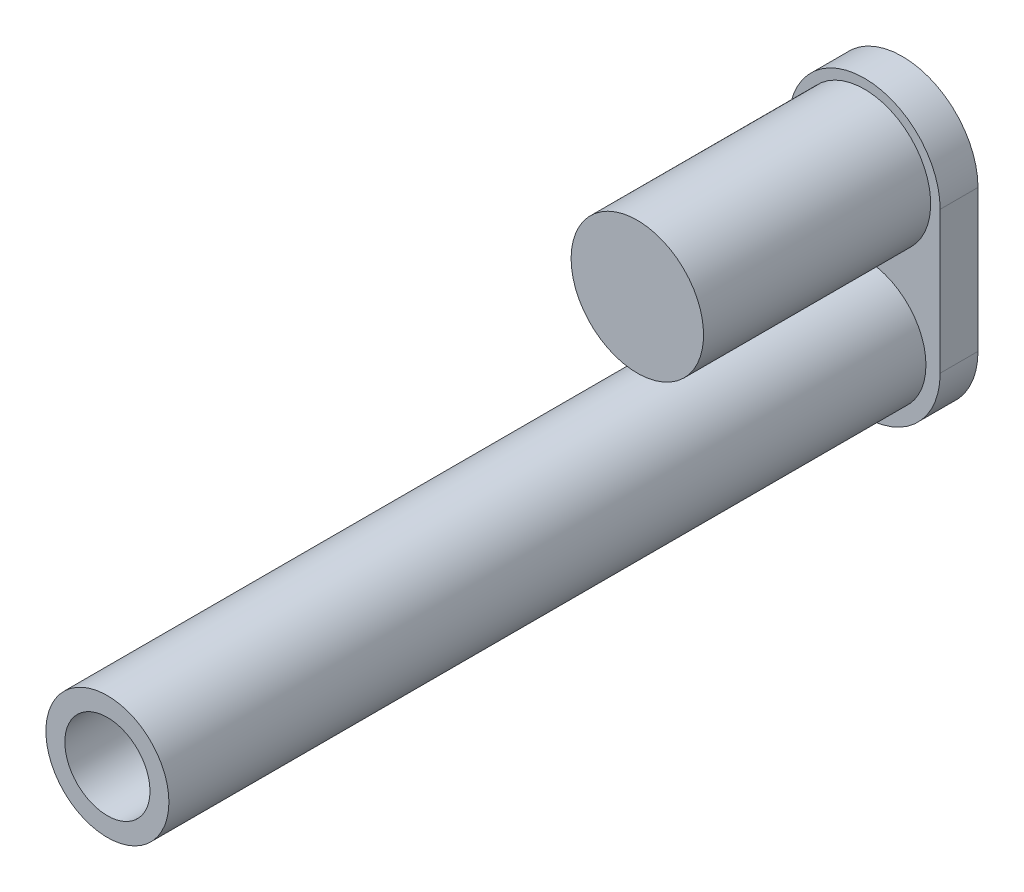
SolidWorks part; units mm, degrees
ref_plane "Front Plane" through (0, 0, 0) normal (0, 0, 1) x (1, 0, 0)
ref_plane "Top Plane" through (0, 0, 0) normal (0, 1, 0) x (1, 0, 0)
ref_plane "Right Plane" through (0, 0, 0) normal (1, 0, 0) x (0, 0, -1)
sketch "Sketch1" plane through (0, 0, 0) normal (0, 0, 1) x (1, 0, 0)
  line L0 (0, 0) -> (0, 47.625) construction
  line L1 (-25.4, 0) -> (-25.4, 47.625)
  line L2 (25.4, 0) -> (25.4, 47.625)
  arc A0 (-25.4, 0) -> (25.4, 0) centre (0, 0) ccw
  arc A1 (25.4, 47.625) -> (-25.4, 47.625) centre (0, 47.625) ccw
  point P3 (0, 23.8125)
  dimension "D1" = 25.4
  dimension "D2" = 47.625
extrude "Boss-Extrude1" add sketch "Sketch1" along normal blind 12.7
sketch "Sketch2" plane through (0, 0, 12.7) normal (0, 0, 1) x (1, 0, 0)
  circle A0 centre (0, 47.625) radius 22.225
  dimension "D1" = 44.45
extrude "Boss-Extrude2" add sketch "Sketch2" along normal blind 76.2
sketch "Sketch3" plane through (0, 0, 12.7) normal (0, 0, 1) x (1, 0, 0)
  circle A0 centre (0, 0) radius 20.6375
  dimension "D1" = 41.275
extrude "Boss-Extrude3" add sketch "Sketch3" along normal blind 254
sketch "Sketch4" plane through (0, 0, 266.7) normal (0, 0, 1) x (1, 0, 0)
  circle A2 centre (0, 0) radius 14.2875
  circle A3 centre (0, 0) radius 14.2875
  dimension "D1" = 6.35
extrude "Cut-Extrude1" cut sketch "Sketch4" against normal blind 203.2
sketch "Sketch5" plane through (0, 0, 0) normal (1, 0, 0) x (0, 0, -1)
  line L0 (0, 0) -> (0, 47.625) construction
  line L1 (0, 6.35) -> (12.7, 6.35)
  line L2 (0, 6.35) -> (0, -6.35)
  line L3 (0, -6.35) -> (12.7, -6.35)
  line L4 (12.7, 6.35) -> (12.7, -6.35)
  circle A0 centre (7.9375, 0) radius 3.175
  point P6 (0, 0)
  point P10 (0, 0)
  point P11 (0, 0)
  dimension "D2" = 6.35
  dimension "D1" = 12.7
  dimension "D3" = 7.9375
extrude "Boss-Extrude4" add sketch "Sketch5" along normal blind 6.35 and the other way blind 6.35
